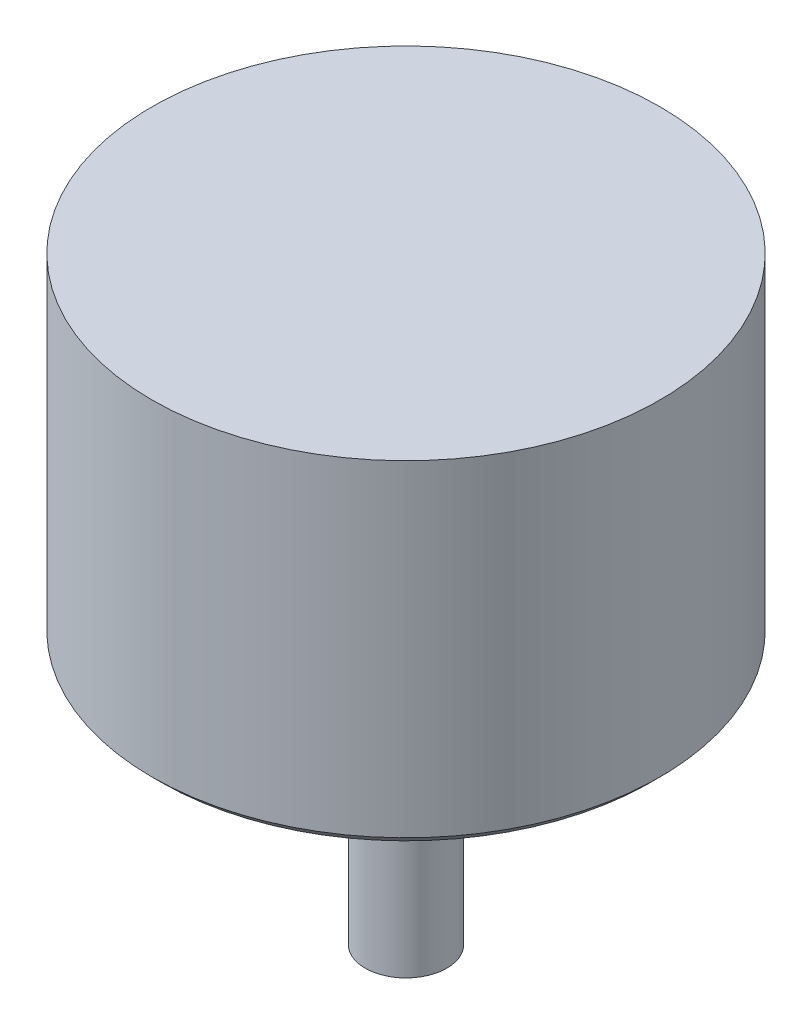
SolidWorks part; units mm, degrees
ref_plane "Front Plane" through (0, 0, 0) normal (0, 0, 1) x (1, 0, 0)
ref_plane "Top Plane" through (0, 0, 0) normal (0, 1, 0) x (1, 0, 0)
ref_plane "Right Plane" through (0, 0, 0) normal (1, 0, 0) x (0, 0, -1)
sketch "Sketch1" plane through (0, 0, 0) normal (0, 1, 0) x (1, 0, 0)
  circle A0 centre (0, 0) radius 14
  dimension "D1" = 28
extrude "Boss-Extrude4" add sketch "Sketch1" along normal blind 19 contours A0
sketch "Sketch7" plane through (0, 0, 0) normal (0, -1, 0) x (1, 0, 0)
  circle A0 centre (0, 0) radius 2.25
extrude "Boss-Extrude5" add sketch "Sketch7" along normal blind 14
sketch "Sketch9" plane through (0, 0, 0) normal (0, -1, 0) x (1, 0, 0)
  circle A0 centre (0, 0) radius 4
extrude "Boss-Extrude8" add sketch "Sketch9" along normal blind 1
sketch "Sketch10" plane through (0, 0, 0) normal (0, 0, 1) x (1, 0, 0)
  line L0 (-4, 0) -> (-14, 0)
  line L1 (-14, 0) -> (-14, 1.0012)
  line L2 (-14, 19) -> (-14, 0) construction
  line L3 (-14, 1.0012) -> (-13.4994, 0.5006)
  line L4 (-13.4994, 0.5006) -> (-4, 0)
revolve "Cut-Revolve9" cut sketch "Sketch10" angle 360 about L0
